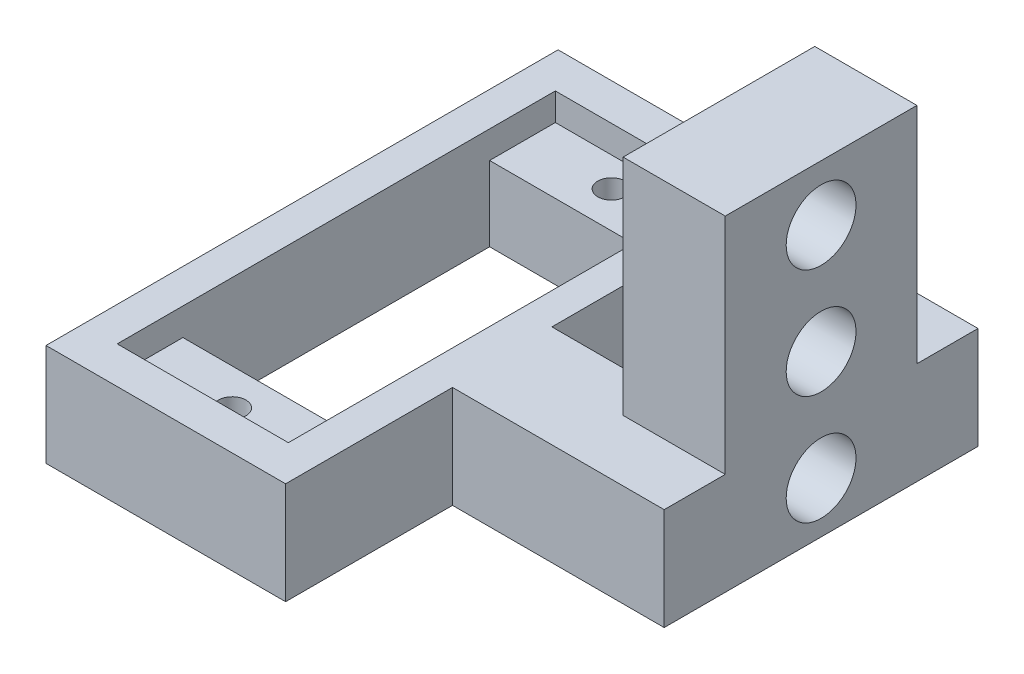
SolidWorks part; units mm, degrees
ref_plane "Front Plane" through (0, 0, 0) normal (0, 0, 1) x (1, 0, 0)
ref_plane "Top Plane" through (0, 0, 0) normal (0, 1, 0) x (1, 0, 0)
ref_plane "Right Plane" through (0, 0, 0) normal (1, 0, 0) x (0, 0, -1)
sketch "Sketch4" plane through (0, 0, 0) normal (0, 1, 0) x (1, 0, 0)
  line L0 (0, 24.3119) -> (0, -27.7936) construction
  line L1 (-27.8941, 0) -> (23.9754, 0) construction
  line L2 (-6.25, -4.95) -> (0, -4.95) construction
  line L3 (8.75, 11.46) -> (24.21, 11.46)
  line L4 (8.55, 4) -> (16.75, 4)
  line L5 (-6.25, 6.25) -> (6.25, 6.25)
  line L6 (6.25, 6.25) -> (6.25, -16.15)
  line L7 (6.25, -16.15) -> (-6.25, -16.15)
  line L8 (-6.25, 6.25) -> (-6.25, -16.15)
  line L9 (8.55, 4) -> (8.55, -4)
  line L10 (8.55, -4) -> (16.75, -4)
  line L11 (16.75, 4) -> (16.75, -4)
  line L12 (8.55, 4) -> (16.75, -4) construction
  line L13 (8.55, -4) -> (16.75, 4) construction
  line L14 (-8.75, 13.75) -> (8.75, 13.75)
  line L15 (-8.75, 13.75) -> (-8.75, -23.65)
  line L16 (-8.75, -23.65) -> (8.75, -23.65)
  line L17 (8.75, 13.75) -> (8.75, 11.46)
  line L18 (-8.75, 13.75) -> (8.75, -23.65) construction
  line L19 (-8.75, -23.65) -> (8.75, 13.75) construction
  line L20 (24.21, 11.46) -> (24.21, -11.46)
  line L21 (8.75, -11.46) -> (24.21, -11.46)
  line L22 (8.75, -11.46) -> (8.75, -23.65)
  circle A0 centre (0, 8.9) radius 1
  circle A1 centre (0, -18.8) radius 1
  point P11 (12.65, 0)
  point P17 (0, -16.15)
  point P18 (0, 6.25)
  point P31 (24.21, 0)
  dimension "D7" = 8
  dimension "D8" = 7.5
  dimension "D4" = 27.7
  dimension "D5" = 2
  dimension "D1" = 22.4
  dimension "D2" = 6.25
  dimension "D3" = 6.25
  dimension "D6" = 8.2
  dimension "D9" = 2.5
  dimension "D10" = 12.65
  dimension "D11" = 7.46
  dimension "D12" = 7.46
extrude "Boss-Extrude2" add sketch "Sketch4" along normal blind 7.46
sketch "Sketch8" plane through (0, 7.46, 0) normal (0, 1, 0) x (1, 0, 0)
  line L0 (16.75, 0) -> (24.21, 0) construction
  line L1 (16.75, -4) -> (16.75, 4) construction
  line L2 (24.21, -11.46) -> (24.21, 11.46) construction
  line L3 (16.75, 7) -> (24.21, 7)
  line L4 (16.75, 7) -> (16.75, -7)
  line L5 (24.21, 7) -> (24.21, -7)
  line L6 (16.75, -7) -> (24.21, -7)
  dimension "D1" = 7
extrude "Boss-Extrude4" add sketch "Sketch8" along normal blind 16.34
sketch "Sketch9" plane through (16.75, 0, 0) normal (-1, 0, 0) x (0, 0, 1)
  line L0 (0, 0) -> (0, 23.8) construction
  line L1 (4, 0) -> (-4, 0) construction
  line L2 (-7, 23.8) -> (7, 23.8) construction
  line L3 (-4, 3.73) -> (4, 3.73) construction
  line L4 (-4, 7.46) -> (-4, 0) construction
  line L5 (4, 7.46) -> (4, 0) construction
  circle A0 centre (0, 3.73) radius 2.55
  circle A1 centre (0, 11.73) radius 2.55
  circle A2 centre (0, 19.73) radius 2.55
  dimension "D1" = 5.1
  dimension "D3" = 8
  dimension "D2" = 3
extrude "Cut-Extrude2" cut sketch "Sketch9" against normal through all
sketch "Sketch12" plane through (0, 7.46, 0) normal (0, 1, 0) x (1, 0, 0)
  line L0 (6.25, -4.95) -> (-6.25, -4.95) construction
  line L1 (6.25, -16.15) -> (6.25, 6.25) construction
  line L2 (-6.25, 6.25) -> (-6.25, -16.15) construction
  line L3 (0, 6.25) -> (0, -16.15) construction
  line L4 (6.25, 6.25) -> (-6.25, 6.25) construction
  line L5 (-6.25, -16.15) -> (6.25, -16.15) construction
  line L7 (6.25, 11.05) -> (-6.25, 11.05)
  line L8 (6.25, 11.05) -> (6.25, -20.95)
  line L9 (6.25, -20.95) -> (-6.25, -20.95)
  line L10 (-6.25, 11.05) -> (-6.25, -20.95)
  line L11 (6.25, 11.05) -> (-6.25, -20.95) construction
  line L12 (6.25, -20.95) -> (-6.25, 11.05) construction
  point P12 (0, -4.95)
  dimension "D1" = 32
  dimension "D2" = 12.5
extrude "Cut-Extrude5" cut sketch "Sketch12" against normal blind 2
